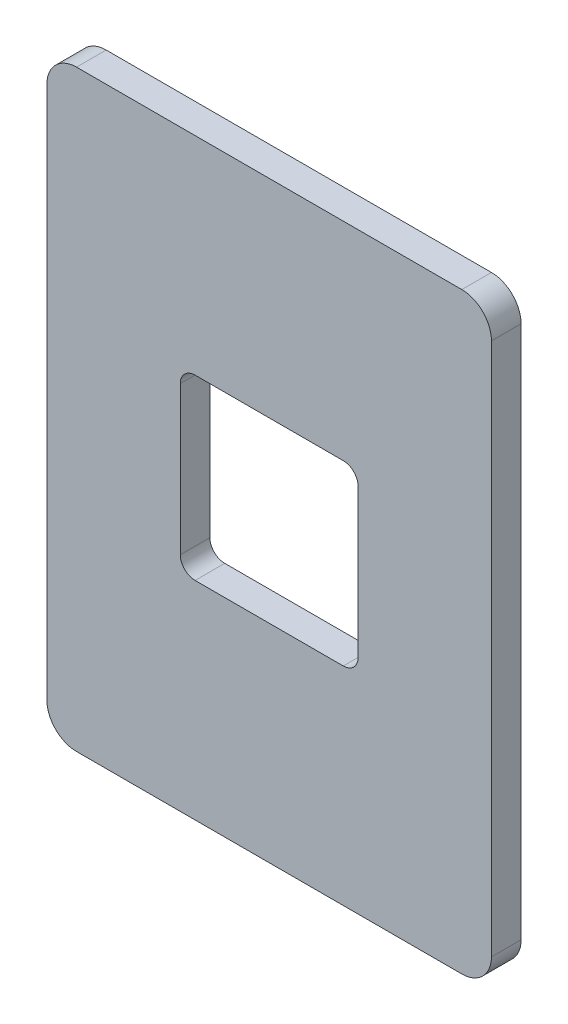
SolidWorks part; units mm, degrees
ref_plane "Plan de face" through (0, 0, 0) normal (0, 0, 1) x (1, 0, 0)
ref_plane "Plan de dessus" through (0, 0, 0) normal (0, 1, 0) x (1, 0, 0)
ref_plane "Plan de droite" through (0, 0, 0) normal (1, 0, 0) x (0, 0, -1)
sketch "Esquisse1" plane through (0, 0, 0) normal (0, 0, 1) x (1, 0, 0)
  line L1 (-15, -20) -> (15, -20)
  line L2 (-15, -20) -> (-15, 20)
  line L3 (-15, 20) -> (15, 20)
  line L4 (15, -20) -> (15, 20)
  line L5 (-15, -20) -> (15, 20) construction
  line L6 (-15, 20) -> (15, -20) construction
  point P0 (0, 0)
  dimension "D1" = 30
  dimension "D2" = 40
extrude "Boss.-Extru.1" add sketch "Esquisse1" along normal blind 2
fillet "Congé1" radius 2 4 edges at (15, -20, 1) (-15, -20, 1) (-15, 20, 1) (15, 20, 1)
sketch "Esquisse2" plane through (0, 0, 0) normal (0, 0, -1) x (-1, 0, 0)
  line L0 (0, 20) -> (0, -20) construction
  line L1 (-13, 20) -> (13, 20) construction
  line L2 (13, -20) -> (-13, -20) construction
  circle A0 centre (0, 0) radius 5
  dimension "D1" = 10
sketch "Esquisse3" plane through (0, 0, 0) normal (0, 0, -1) x (-1, 0, 0)
  line L1 (-6, -6) -> (6, -6)
  line L2 (-6, -6) -> (-6, 6)
  line L3 (-6, 6) -> (6, 6)
  line L4 (6, -6) -> (6, 6)
  line L5 (-6, -6) -> (6, 6) construction
  line L6 (-6, 6) -> (6, -6) construction
  point P0 (0, 0)
  dimension "D1" = 12
  dimension "D2" = 12
extrude "Enlèv. mat.-Extru.1" cut sketch "Esquisse3" against normal blind 10
fillet "Congé2" radius 1 4 edges at (6, 6, 1) (6, -6, 1) (-6, -6, 1) (-6, 6, 1)
